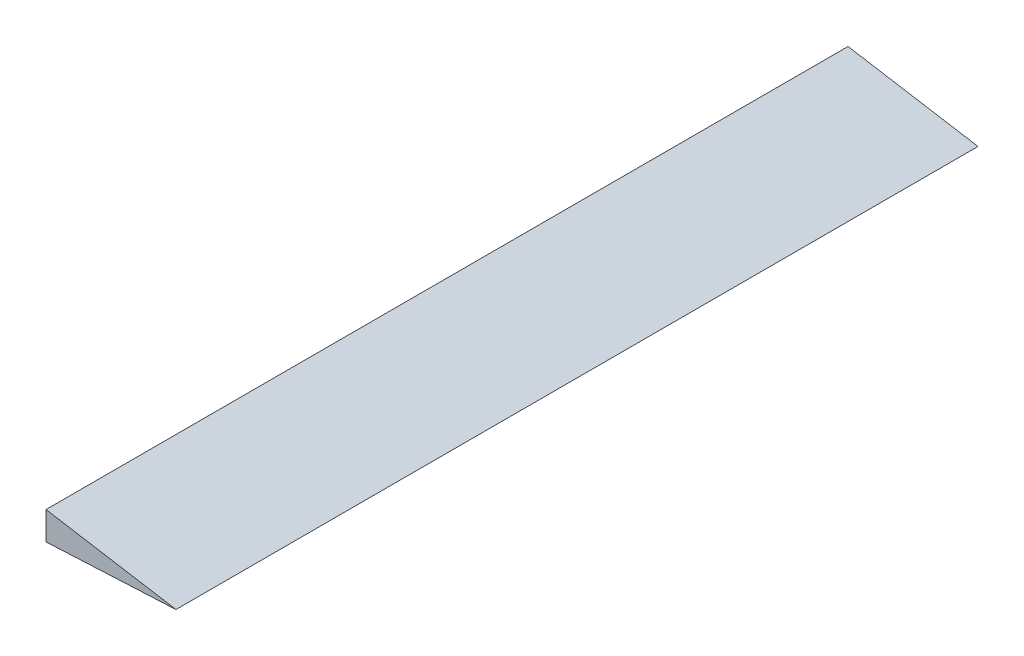
SolidWorks part; units mm, degrees
material "Balsa"
ref_plane "Front Plane" through (0, 0, 0) normal (0, 0, 1) x (1, 0, 0)
ref_plane "Top Plane" through (0, 0, 0) normal (0, 1, 0) x (1, 0, 0)
ref_plane "Right Plane" through (0, 0, 0) normal (1, 0, 0) x (0, 0, -1)
sketch "Sketch1" plane through (0, 0, 0) normal (0, 0, 1) x (1, 0, 0)
  line L0 (306.8496, -2.5161) -> (306.8496, 8.4499) construction
  line L1 (306.8496, -2.5161) -> (306.8496, 8.4499)
  line L2 (306.8496, 8.4499) -> (357.6496, 0)
  line L3 (306.8496, -2.5161) -> (357.6496, 0)
  spline S0 degree 3 poles (354.9573, 0.0431) (358.3317, -0.0432) (354.9981, 0.2938) (352.3707, 0.8024) (346.1763, 1.8676) (338.7813, 3.2655) (329.3081, 4.8919) (318.2482, 6.6648) (305.5952, 8.6507) (291.564, 10.8193) (276.34, 13.1505) (260.1392, 15.5903) (243.1815, 18.0913) (225.699, 20.6027) (207.9209, 23.0318) (190.087, 25.3152) (172.4086, 27.3328) (155.0467, 28.9096) (138.1258, 29.947) (121.7437, 30.3922) (105.9899, 30.2108) (90.9433, 29.4155) (76.6903, 28.0308) (63.3272, 26.1868) (50.9728, 23.9485) (39.7523, 21.3791) (29.7714, 18.545) (21.1318, 15.5018) (13.8914, 12.3237) (8.1391, 9.1075) (3.8158, 5.9031) (1.1802, 2.9693) (-0.4877, -0.018) (1.2572, -2.9285) (4.805, -4.6528) (9.8754, -6.6365) (16.78, -8.2511) (25.3535, -9.7017) (35.5828, -10.8813) (47.3622, -11.8027) (60.5842, -12.4624) (75.1117, -12.8607) (90.7897, -13.0132) (107.4435, -12.9137) (124.9052, -12.5651) (143.0256, -11.8868) (161.6617, -10.9405) (180.6424, -9.8572) (199.7442, -8.7119) (218.721, -7.5525) (237.3263, -6.4253) (255.3201, -5.3536) (272.4652, -4.367) (288.5372, -3.4753) (303.3148, -2.6922) (316.6121, -2.0207) (328.2104, -1.4385) (338.1246, -0.9102) (345.8395, -0.4061) (352.2525, -0.129) (354.9573, 0.0431) (358.3317, -0.0432) (354.9981, 0.2938) knots -0.015092 -0.006889 -0.001754 0 0.001748 0.006827 0.01488 0.025572 0.038694 0.054171 0.071834 0.091435 0.112685 0.135293 0.158944 0.183315 0.20807 0.232879 0.257399 0.281384 0.304706 0.327241 0.348897 0.369607 0.389308 0.407886 0.425177 0.441027 0.4553 0.467904 0.478752 0.487814 0.49509 0.500617 0.504451 0.507804 0.513091 0.520546 0.530249 0.542214 0.556382 0.572656 0.590895 0.610925 0.632536 0.655496 0.679547 0.704499 0.730211 0.756436 0.782837 0.809062 0.834776 0.859641 0.883338 0.905541 0.925965 0.944326 0.960366 0.973929 0.984908 0.993111 0.998246 1 1.001748 1.006827 1.01488 only from (357.6496, 0) to (357.6496, 0) construction
  spline S1 degree 3 poles (354.9573, 0.0431) (358.3317, -0.0432) (354.9981, 0.2938) (352.3707, 0.8024) (346.1763, 1.8676) (338.7813, 3.2655) (329.3081, 4.8919) (318.2482, 6.6648) (305.5952, 8.6507) (291.564, 10.8193) (276.34, 13.1505) (260.1392, 15.5903) (243.1815, 18.0913) (225.699, 20.6027) (207.9209, 23.0318) (190.087, 25.3152) (172.4086, 27.3328) (155.0467, 28.9096) (138.1258, 29.947) (121.7437, 30.3922) (105.9899, 30.2108) (90.9433, 29.4155) (76.6903, 28.0308) (63.3272, 26.1868) (50.9728, 23.9485) (39.7523, 21.3791) (29.7714, 18.545) (21.1318, 15.5018) (13.8914, 12.3237) (8.1391, 9.1075) (3.8158, 5.9031) (1.1802, 2.9693) (-0.4877, -0.018) (1.2572, -2.9285) (4.805, -4.6528) (9.8754, -6.6365) (16.78, -8.2511) (25.3535, -9.7017) (35.5828, -10.8813) (47.3622, -11.8027) (60.5842, -12.4624) (75.1117, -12.8607) (90.7897, -13.0132) (107.4435, -12.9137) (124.9052, -12.5651) (143.0256, -11.8868) (161.6617, -10.9405) (180.6424, -9.8572) (199.7442, -8.7119) (218.721, -7.5525) (237.3263, -6.4253) (255.3201, -5.3536) (272.4652, -4.367) (288.5372, -3.4753) (303.3148, -2.6922) (316.6121, -2.0207) (328.2104, -1.4385) (338.1246, -0.9102) (345.8395, -0.4061) (352.2525, -0.129) (354.9573, 0.0431) (358.3317, -0.0432) (354.9981, 0.2938) knots -0.015092 -0.006889 -0.001754 0 0.001748 0.006827 0.01488 0.025572 0.038694 0.054171 0.071834 0.091435 0.112685 0.135293 0.158944 0.183315 0.20807 0.232879 0.257399 0.281384 0.304706 0.327241 0.348897 0.369607 0.389308 0.407886 0.425177 0.441027 0.4553 0.467904 0.478752 0.487814 0.49509 0.500617 0.504451 0.507804 0.513091 0.520546 0.530249 0.542214 0.556382 0.572656 0.590895 0.610925 0.632536 0.655496 0.679547 0.704499 0.730211 0.756436 0.782837 0.809062 0.834776 0.859641 0.883338 0.905541 0.925965 0.944326 0.960366 0.973929 0.984908 0.993111 0.998246 1 1.001748 1.006827 1.01488 only from (357.6496, 0) to (357.6496, 0)
sketch "Sketch2" plane through (0, 0, -761.9997) normal (0, 0, -1) x (-1, 0, 0)
  line L0 (-306.8496, -2.5161) -> (-306.8496, 8.4499) construction
  line L1 (-306.8496, -2.5161) -> (-357.6496, 0) construction
  line L2 (-306.8496, 8.4499) -> (-357.6496, 0) construction
  line L3 (-306.8496, -2.5161) -> (-306.8496, 8.4499)
  line L4 (-306.8496, -2.5161) -> (-357.6496, 0)
  line L5 (-306.8496, 8.4499) -> (-357.6496, 0)
extrude "Boss-Extrude2" add sketch "Sketch2" against normal blind 313.5173
